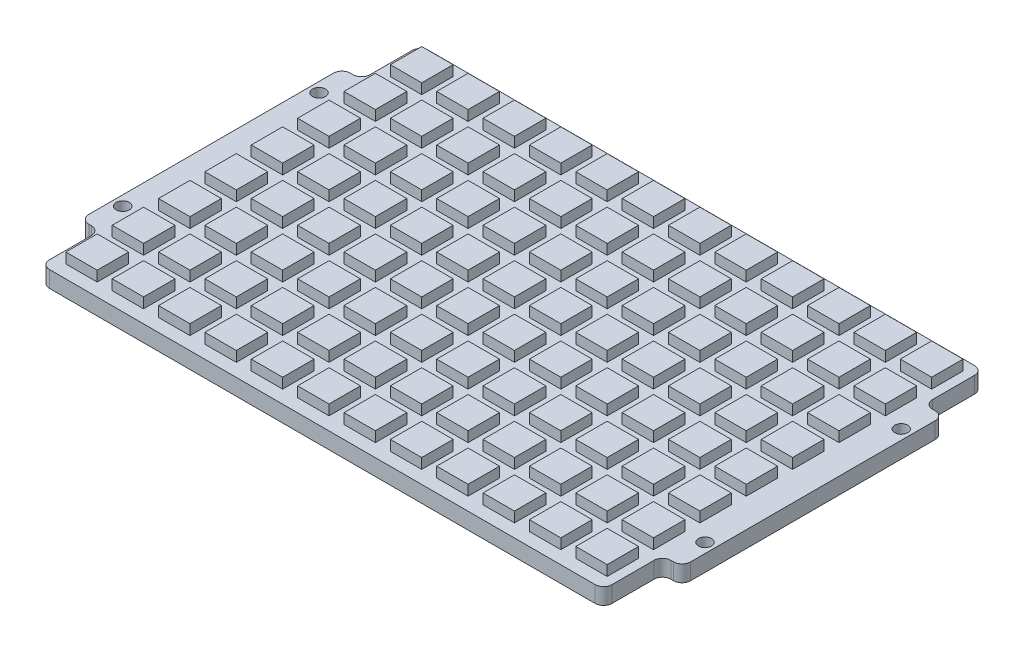
SolidWorks part; units mm, degrees
ref_plane "Front Plane" through (0, 0, 0) normal (0, 0, 1) x (1, 0, 0)
ref_plane "Top Plane" through (0, 0, 0) normal (0, 1, 0) x (1, 0, 0)
ref_plane "Right Plane" through (0, 0, 0) normal (1, 0, 0) x (0, 0, -1)
sketch "Sketch1" plane through (0, 0, 0) normal (0, 1, 0) x (1, 0, 0)
  line L1 (-54.61, -36.83) -> (54.61, -36.83)
  line L2 (-54.61, -36.83) -> (-54.61, 36.83)
  line L3 (-54.61, 36.83) -> (54.61, 36.83)
  line L4 (54.61, -36.83) -> (54.61, 36.83)
  line L5 (-54.61, -36.83) -> (54.61, 36.83) construction
  line L6 (-54.61, 36.83) -> (54.61, -36.83) construction
  point P0 (0, 0)
  dimension "D1" = 109.22
  dimension "D2" = 73.66
extrude "Boss-Extrude1" add sketch "Sketch1" against normal blind 3.175
ref_plane "Plane1" through (0, 0, -31.75) normal (0, 0, 1) x (1, 0, 0)
sketch "Sketch2" plane through (0, 0, -31.75) normal (0, 0, 1) x (1, 0, 0)
  line L3 (-49.276, 0) -> (-52.324, 0)
  line L4 (-49.276, 2) -> (-49.276, 0) construction
  line L5 (-52.324, 0) -> (-52.324, 2)
  line L6 (-54.61, 0) -> (54.61, 0) construction
  line L7 (-46.228, 0) -> (-49.276, 0)
  line L8 (-52.324, 2) -> (-49.276, 2)
  line L9 (-49.276, 2) -> (-46.228, 2)
  line L10 (-46.228, 2) -> (-46.228, 0)
  point P5 (-50.8, 0)
  dimension "D1" = 3.048
  dimension "D2" = 2
  dimension "D3" = 50.8
extrude "Boss-Extrude3" add sketch "Sketch2" along normal mid plane 6.096
pattern_linear "LPattern1" count 12 spacing 9 along (1, 0, 0) count 8 spacing 9 along (0, 0, 1) of "Boss-Extrude3"
sketch "Sketch3" plane through (0, 0, 0) normal (0, 1, 0) x (1, 0, 0)
  line L0 (-54.61, 36.83) -> (-54.61, -36.83) construction
  line L1 (-54.61, 25.4) -> (-58.42, 25.4)
  line L2 (-54.61, 25.4) -> (-54.61, -25.4)
  line L3 (-54.61, -25.4) -> (-58.42, -25.4)
  line L4 (-58.42, 25.4) -> (-58.42, -25.4)
  line L5 (0, 0) -> (0, 36.83) construction
  line L6 (54.61, 36.83) -> (-54.61, 36.83) construction
  line L7 (58.42, 25.4) -> (58.42, -25.4)
  line L8 (54.61, -25.4) -> (58.42, -25.4)
  line L9 (54.61, 25.4) -> (54.61, -25.4)
  line L10 (54.61, 25.4) -> (58.42, 25.4)
  circle A0 centre (-56.515, 19.05) radius 1.27
  circle A1 centre (-56.515, -19.05) radius 1.27
  circle A2 centre (56.515, -19.05) radius 1.27
  circle A3 centre (56.515, 19.05) radius 1.27
  point P6 (-58.42, 0)
  point P11 (-56.515, 25.4)
  dimension "D3" = 2.54
  dimension "D1" = 3.81
  dimension "D2" = 50.8
  dimension "D4" = 19.05
  dimension "D5" = 2
extrude "Boss-Extrude2" add sketch "Sketch3" against normal blind 3.175
fillet "Fillet1" radius 1.651 12 edges at (54.61, -1.5875, -36.83) (54.61, -1.5875, -25.4) (58.42, -1.5875, -25.4) (58.42, -1.5875, 25.4) (54.61, -1.5875, 25.4) (54.61, -1.5875, 36.83) (-54.61, -1.5875, 36.83) (-54.61, -1.5875, 25.4) (-58.42, -1.5875, 25.4) (-58.42, -1.5875, -25.4) (-54.61, -1.5875, -25.4) (-54.61, -1.5875, -36.83)
